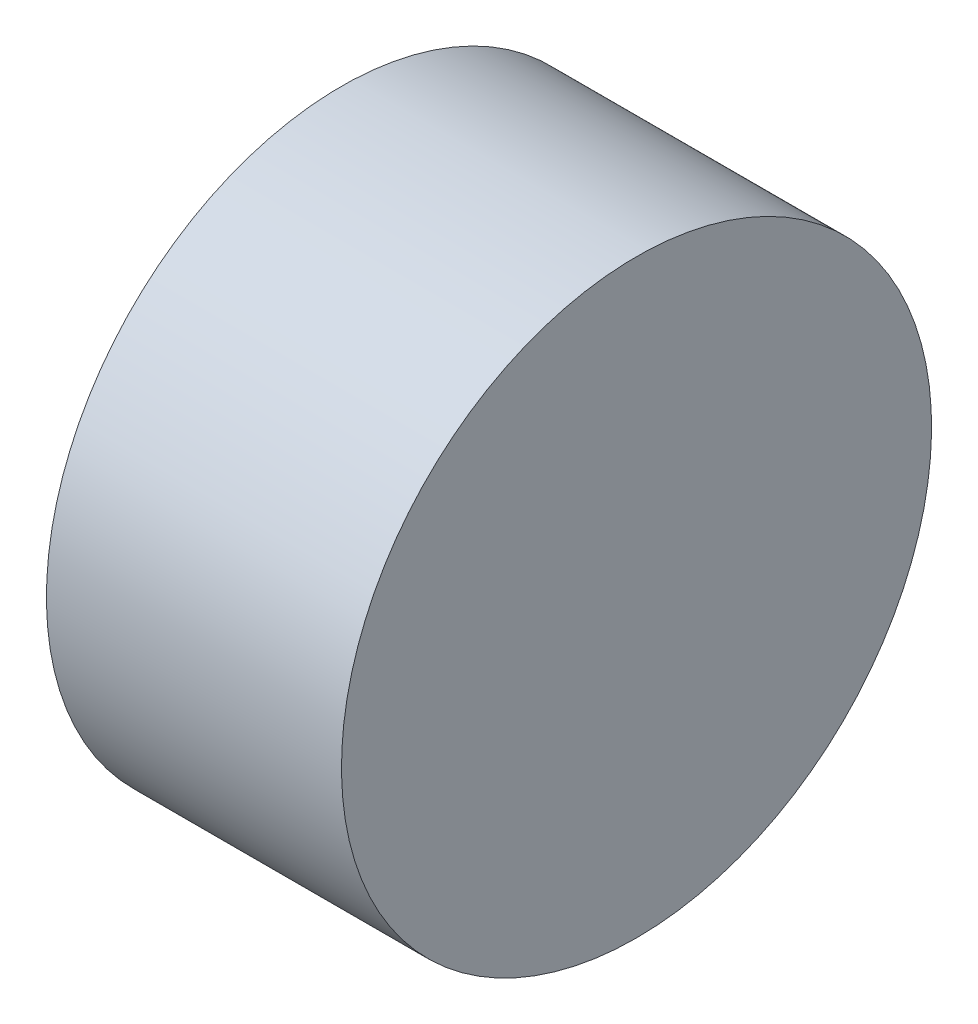
SolidWorks part; units mm, degrees
ref_plane "Front Plane" through (0, 0, 0) normal (0, 0, 1) x (1, 0, 0)
ref_plane "Top Plane" through (0, 0, 0) normal (0, 1, 0) x (1, 0, 0)
ref_plane "Right Plane" through (0, 0, 0) normal (1, 0, 0) x (0, 0, -1)
sketch "Sketch2" plane through (0, 0, 0) normal (0, 0, 1) x (1, 0, 0)
  line L0 (50.8, -50.8) -> (50.8, 0)
  line L3 (50.8, -50.8) -> (0, -50.8)
  line L6 (0, -50.8) -> (0, -33.02)
  line L7 (0, -33.02) -> (15.24, -33.02)
  line L8 (15.24, -33.02) -> (15.24, 0)
  line L9 (15.24, 0) -> (50.8, 0)
  dimension "D1" = 17.78
  dimension "D2" = 15.24
revolve "Revolve1" add sketch "Sketch2" angle 360 about L9
sketch "Sketch3" plane through (0, 0, 0) normal (0, 0, 1) x (1, 0, 0)
  line L0 (-1.2623, 10.5774) -> (1.2413, -8.1969)
  line L5 (-2.5903, 10.3684) -> (-2.5903, -5.8764)
  circle A0 centre (-2.5903, 14.692) radius 1.905
  circle A1 centre (-2.5903, -10.2) radius 1.905
  arc A2 (-2.5903, -5.8764) -> (1.2413, -8.1969) centre (-2.5903, -10.2) ccw
  arc A3 (-1.2623, 10.5774) -> (-2.5903, 10.3684) centre (-2.5903, 14.692) ccw
  dimension "D1" = 24.892
  dimension "D2" = 3.81
extrude "Extrude2" add sketch "Sketch3" along normal mid plane 12.7 separate body
sketch "Sketch4" plane through (0, 0, 0) normal (0, 0, 1) x (1, 0, 0)
  line L0 (-12.7503, 7.3514) -> (-12.7503, -2.8594)
  line L1 (-2.5903, 14.692) -> (-2.5903, -17.8255) construction
  line L2 (-12.7503, 7.3514) -> (-12.7503, -2.8594) construction
  arc A0 (-12.7503, 7.3514) -> (-12.7503, -2.8594) centre (-12.7503, 2.246) ccw
  dimension "D1" = 5.1054
  dimension "D2" = 10.16
revolve "Revolve2" add sketch "Sketch4" angle 360 about L2
